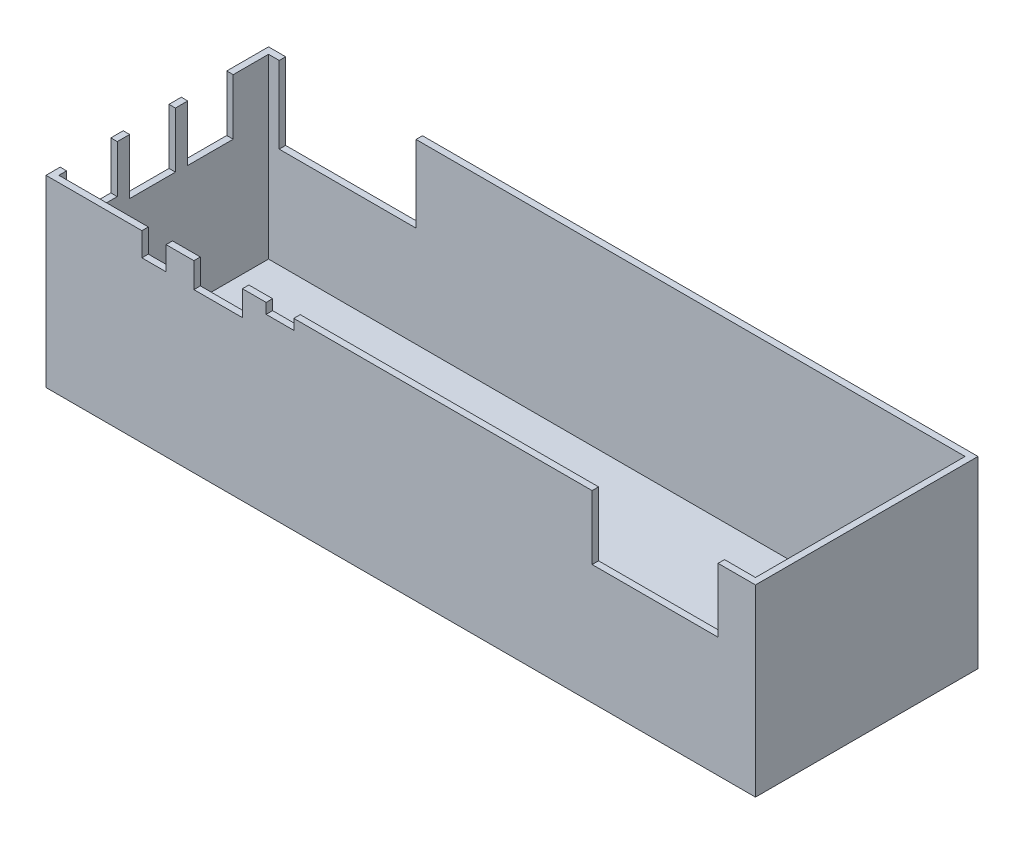
SolidWorks part; units mm, degrees
other "trou raspberry 4"
ref_plane "Plan de face" through (0, 0, 0) normal (0, 0, 1) x (1, 0, 0)
ref_plane "Plan de dessus" through (0, 0, 0) normal (0, 1, 0) x (1, 0, 0)
ref_plane "Plan de droite" through (0, 0, 0) normal (1, 0, 0) x (0, 0, -1)
sketch "Esquisse1" plane through (0, 0, 0) normal (0, 0, 1) x (1, 0, 0)
  line L1 (-72.2022, 43.1798) -> (147.7978, 43.1798)
  line L2 (-72.2022, 43.1798) -> (-72.2022, -13.8202)
  line L3 (-72.2022, -13.8202) -> (147.7978, -13.8202)
  line L4 (147.7978, 43.1798) -> (147.7978, -13.8202)
  dimension "D1" = 220
  dimension "D2" = 57
extrude "Boss.-Extru.1" add sketch "Esquisse1" along normal blind 69
shell "Coque1" thickness 2
sketch "Esquisse2" plane through (0, 0, 0) normal (0, 0, -1) x (-1, 0, 0)
  line L0 (-147.7978, 43.1798) -> (72.2022, 43.1798) construction
  line L1 (66.8892, 43.1798) -> (24.4583, 43.1798)
  line L2 (66.8892, 43.1798) -> (66.8892, 19.3603)
  line L3 (66.8892, 19.3603) -> (24.4583, 19.3603)
  line L4 (24.4583, 43.1798) -> (24.4583, 19.3603)
extrude "Trou cables" cut sketch "Esquisse2" against normal blind 10
sketch "Esquisse4" plane through (0, 0, 69) normal (0, 0, 1) x (1, 0, 0)
  line L0 (147.7978, 43.1798) -> (-72.2022, 43.1798) construction
  line L1 (136.2061, 43.1798) -> (97.1429, 43.1798)
  line L2 (136.2061, 43.1798) -> (136.2061, 23.3281)
  line L3 (136.2061, 23.3281) -> (97.1429, 23.3281)
  line L4 (97.1429, 43.1798) -> (97.1429, 23.3281)
  point P6 (94.874, 27.6073)
  point P7 (97.1429, 23.3281)
extrude "trou bornier" cut sketch "Esquisse4" against normal blind 10
sketch "Esquisse5" plane through (-72.2022, 0, 0) normal (-1, 0, 0) x (0, 0, 1)
  line L0 (69, 43.1798) -> (0, 43.1798) construction
  line L1 (64.6066, 28.4077) -> (48.906, 28.4077)
  line L2 (64.6066, 28.4077) -> (64.6066, 43.1798)
  line L3 (64.6066, 43.1798) -> (48.906, 43.1798)
  line L4 (48.906, 28.4077) -> (48.906, 43.1798)
extrude "trou raspberry 1" cut sketch "Esquisse5" against normal blind 10
sketch "Esquisse6" plane through (-72.2022, 0, 0) normal (-1, 0, 0) x (0, 0, 1)
  line L0 (48.906, 43.1798) -> (0, 43.1798) construction
  line L1 (45.055, 25.963) -> (30.8675, 25.963)
  line L2 (45.055, 25.963) -> (45.055, 43.1798)
  line L3 (45.055, 43.1798) -> (30.8675, 43.1798)
  line L4 (30.8675, 25.963) -> (30.8675, 43.1798)
extrude "trou raspberry 2" cut sketch "Esquisse6" against normal blind 10
sketch "Esquisse7" plane through (-72.2022, 0, 0) normal (-1, 0, 0) x (0, 0, 1)
  line L0 (30.8675, 43.1798) -> (0, 43.1798) construction
  line L1 (27.0496, 25.8491) -> (12.9486, 25.8491)
  line L2 (27.0496, 25.8491) -> (27.0496, 43.1798)
  line L3 (27.0496, 43.1798) -> (12.9486, 43.1798)
  line L4 (12.9486, 25.8491) -> (12.9486, 43.1798)
extrude "trou raspberry 3" cut sketch "Esquisse7" against normal blind 10
sketch "Esquisse8" plane through (0, 0, 69) normal (0, 0, 1) x (1, 0, 0)
  line L0 (11.7978, 43.1798) -> (-67.2022, 43.1798) construction
  line L1 (-34.9741, 35.8778) -> (-42.4725, 35.8778)
  line L2 (-34.9741, 35.8778) -> (-34.9741, 43.1798)
  line L3 (-34.9741, 43.1798) -> (-42.4725, 43.1798)
  line L4 (-42.4725, 35.8778) -> (-42.4725, 43.1798)
extrude "trou raspberry 4" cut sketch "Esquisse8" against normal blind 10
sketch "Esquisse9" plane through (0, 0, 69) normal (0, 0, 1) x (1, 0, 0)
  line L0 (97.1429, 43.1798) -> (-34.9741, 43.1798) construction
  line L1 (-11.2911, 35.4095) -> (-26.343, 35.4095)
  line L2 (-11.2911, 35.4095) -> (-11.2911, 43.1798)
  line L3 (-11.2911, 43.1798) -> (-26.343, 43.1798)
  line L4 (-26.343, 35.4095) -> (-26.343, 43.1798)
extrude "trou raspberry 5" cut sketch "Esquisse9" against normal blind 10
sketch "Esquisse10" plane through (0, 0, 69) normal (0, 0, 1) x (1, 0, 0)
  line L0 (97.1429, 43.1798) -> (-11.2911, 43.1798) construction
  line L1 (4.6318, 39.9675) -> (-3.9408, 39.9675)
  line L2 (4.6318, 39.9675) -> (4.6318, 43.1798)
  line L3 (4.6318, 43.1798) -> (-3.9408, 43.1798)
  line L4 (-3.9408, 39.9675) -> (-3.9408, 43.1798)
extrude "trou raspberry 6" cut sketch "Esquisse10" against normal blind 10
